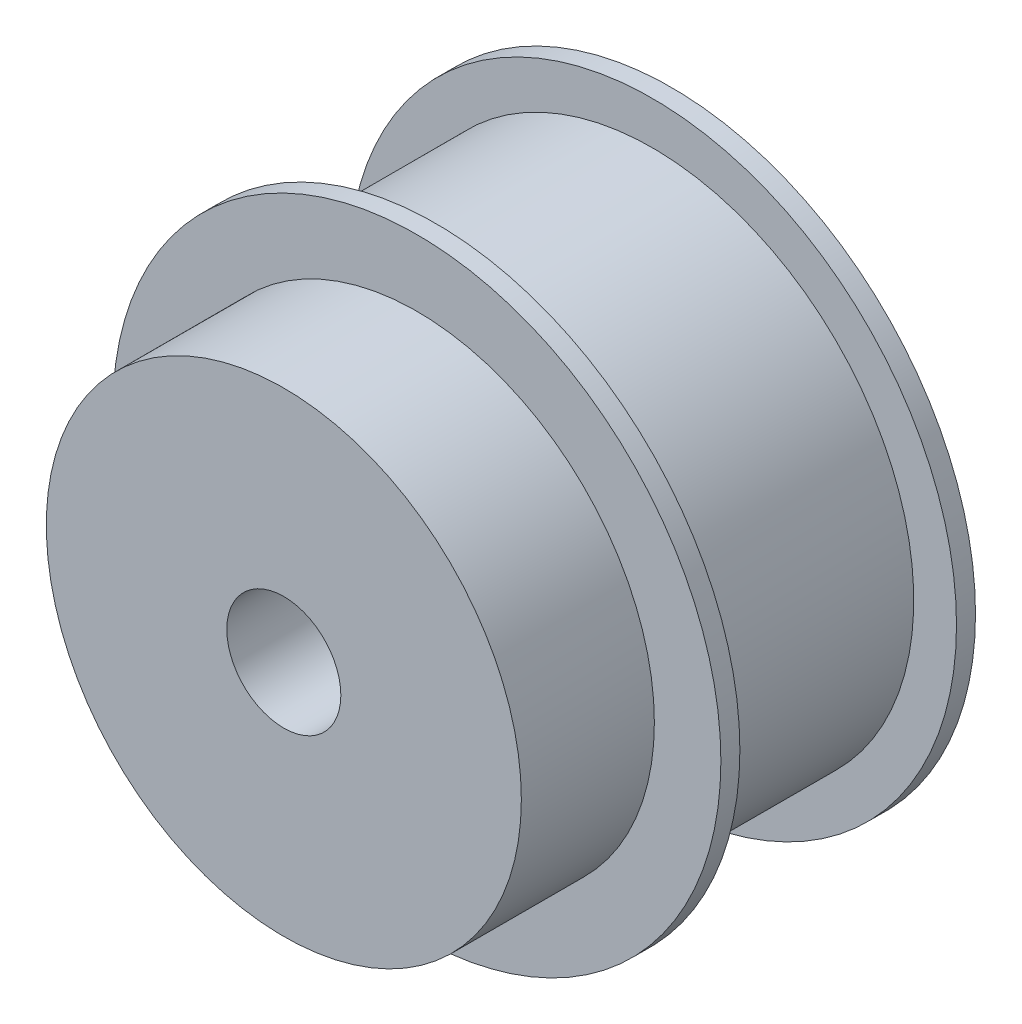
SolidWorks part; units mm, degrees
ref_plane "Plan de face" through (0, 0, 0) normal (0, 0, 1) x (1, 0, 0)
ref_plane "Plan de dessus" through (0, 0, 0) normal (0, 1, 0) x (1, 0, 0)
ref_plane "Plan de droite" through (0, 0, 0) normal (1, 0, 0) x (0, 0, -1)
sketch "Esquisse1" plane through (0, 0, 0) normal (0, 0, 1) x (1, 0, 0)
  circle A0 centre (0, 0) radius 13.75
extrude "Boss.-Extru.1" add sketch "Esquisse1" along normal blind 11.4
sketch "Esquisse2" plane through (0, 0, 11.4) normal (0, 0, 1) x (1, 0, 0)
  circle A0 centre (0, 0) radius 16
extrude "Boss.-Extru.2" add sketch "Esquisse2" along normal blind 1
sketch "Esquisse3" plane through (0, 0, 0) normal (0, 0, -1) x (-1, 0, 0)
  circle A0 centre (0, 0) radius 16
extrude "Boss.-Extru.3" add sketch "Esquisse3" along normal blind 1
sketch "Esquisse4" plane through (0, 0, 12.4) normal (0, 0, 1) x (1, 0, 0)
  circle A0 centre (0, 0) radius 12.5
extrude "Boss.-Extru.4" add sketch "Esquisse4" along normal blind 7
sketch "Esquisse5" plane through (0, 0, -1) normal (0, 0, -1) x (-1, 0, 0)
  circle A0 centre (0, 0) radius 3
extrude "Enlèv. mat.-Extru.1" cut sketch "Esquisse5" against normal blind 30
